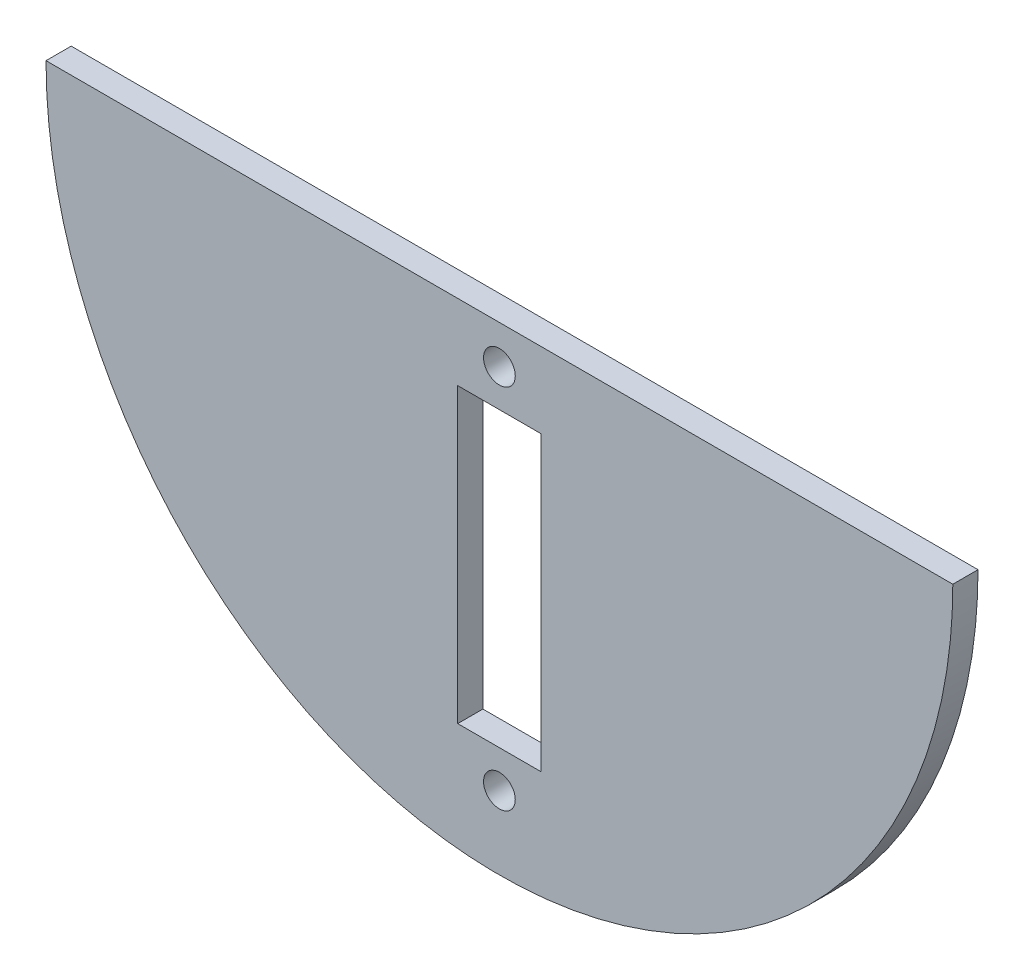
SolidWorks part; units mm, degrees
ref_plane "Front Plane" through (0, 0, 0) normal (0, 0, 1) x (1, 0, 0)
ref_plane "Top Plane" through (0, 0, 0) normal (0, 1, 0) x (1, 0, 0)
ref_plane "Right Plane" through (0, 0, 0) normal (1, 0, 0) x (0, 0, -1)
sketch "Sketch1" plane through (0, 0, 0) normal (0, 0, 1) x (1, 0, 0)
  line L4 (-107.625, 96.1282) -> (-99.2176, 96.1282)
  line L5 (-107.625, 96.1282) -> (-107.625, 125.643)
  line L6 (-107.625, 125.643) -> (-99.2176, 125.643)
  line L7 (-99.2176, 125.643) -> (-99.2176, 96.1282)
  line L8 (-149.1413, 133.263) -> (-57.7013, 133.263)
  circle A2 centre (-103.4213, 129.393) radius 1.6
  circle A3 centre (-103.4213, 92.3782) radius 1.6
  ellipse E1 centre (-103.4213, 133.263) end of major axis (-103.4213, 181.523) minor radius 45.72 (-149.1413, 133.263) -> (-57.7013, 133.263) ccw
extrude "Boss-Extrude1" add sketch "Sketch1" along normal blind 2.54
